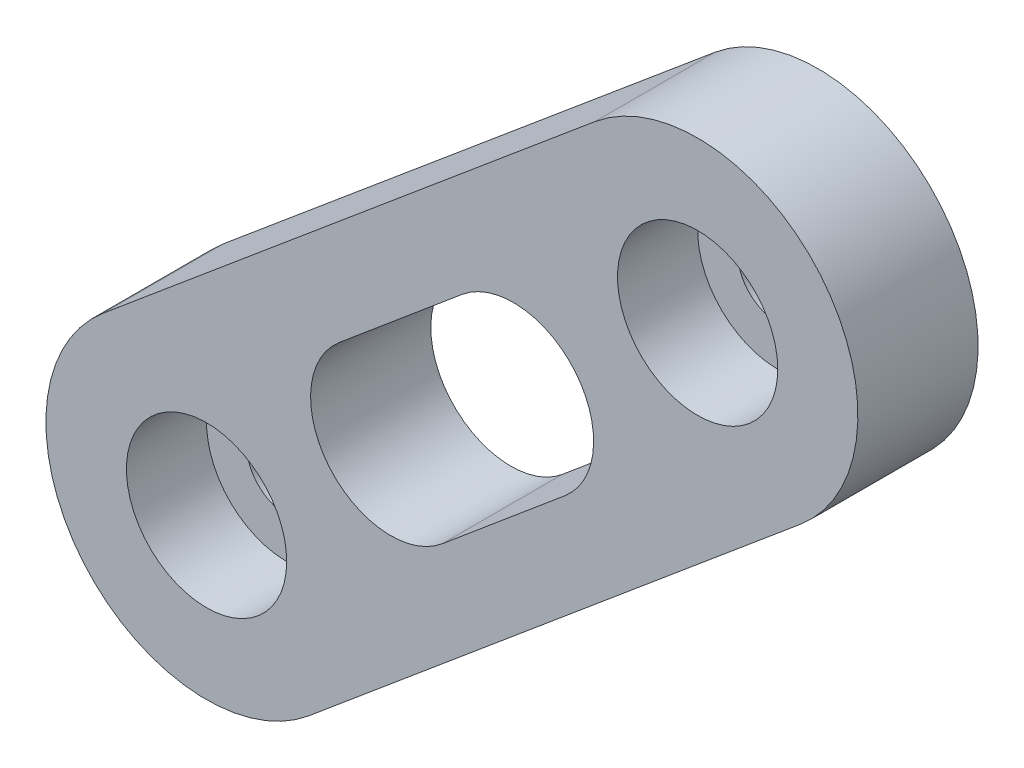
SolidWorks part; units mm, degrees
ref_plane "Front Plane" through (0, 0, 0) normal (0, 0, 1) x (1, 0, 0)
ref_plane "Top Plane" through (0, 0, 0) normal (0, 1, 0) x (1, 0, 0)
ref_plane "Right Plane" through (0, 0, 0) normal (1, 0, 0) x (0, 0, -1)
sketch "Sketch1" plane through (0, 0, 0) normal (0, 0, 1) x (1, 0, 0)
  line L0 (0, 0) -> (179.8502, 0) construction
  line L1 (8.1835, 0) -> (451.863, 372.2913) construction
  line L2 (451.863, 372.2913) -> (517.508, 0) construction
  line L5 (416.0979, 375.4381) -> (338.2035, 310.2076)
  line L7 (448.7131, 336.4909) -> (370.8188, 271.2604)
  line L9 (403.2192, 331.4743) -> (383.7617, 315.1475) construction
  line L10 (411.3826, 321.7456) -> (391.9251, 305.4188)
  line L11 (395.0558, 341.2031) -> (375.5983, 324.8763)
  line L12 (354.5754, 290.6573) -> (338.2035, 310.2076) construction
  line L13 (354.5754, 290.6573) -> (370.8188, 271.2604) construction
  line L14 (416.0979, 375.4381) -> (448.7131, 336.4909) construction
  arc A0 (411.3826, 321.7456) -> (395.0558, 341.2031) centre (403.2192, 331.4743) ccw
  arc A1 (375.5983, 324.8763) -> (391.9251, 305.4188) centre (383.7617, 315.1475) ccw
  circle A2 centre (354.5754, 290.6573) radius 6.35
  arc A3 (338.2035, 310.2076) -> (370.8188, 271.2604) centre (354.5112, 290.734) ccw
  circle A4 centre (432.4055, 355.9645) radius 6.35
  arc A5 (416.0979, 375.4381) -> (448.7131, 336.4909) centre (432.4055, 355.9645) cw
  point P12 (393.4904, 323.3109)
  point P24 (432.4055, 355.9645)
  dimension "D6" = 12.7
  dimension "D7" = 12.7
  dimension "D4" = 25.4
  dimension "D3" = 25.4
  dimension "D1" = 40
  dimension "D2" = 80
  dimension "D5" = 25.4
  dimension "D8" = 38.1
  dimension "D9" = 38.1
extrude "Boss-Extrude1" add sketch "Sketch1" along normal blind 19.05
sketch "Sketch2" plane through (0, 0, 19.05) normal (0, 0, 1) x (1, 0, 0)
  circle A0 centre (354.5754, 290.6573) radius 12.7
  circle A1 centre (432.4055, 355.9645) radius 12.7
  dimension "D1" = 25.4
extrude "Cut-Extrude1" cut sketch "Sketch2" against normal blind 12.7
